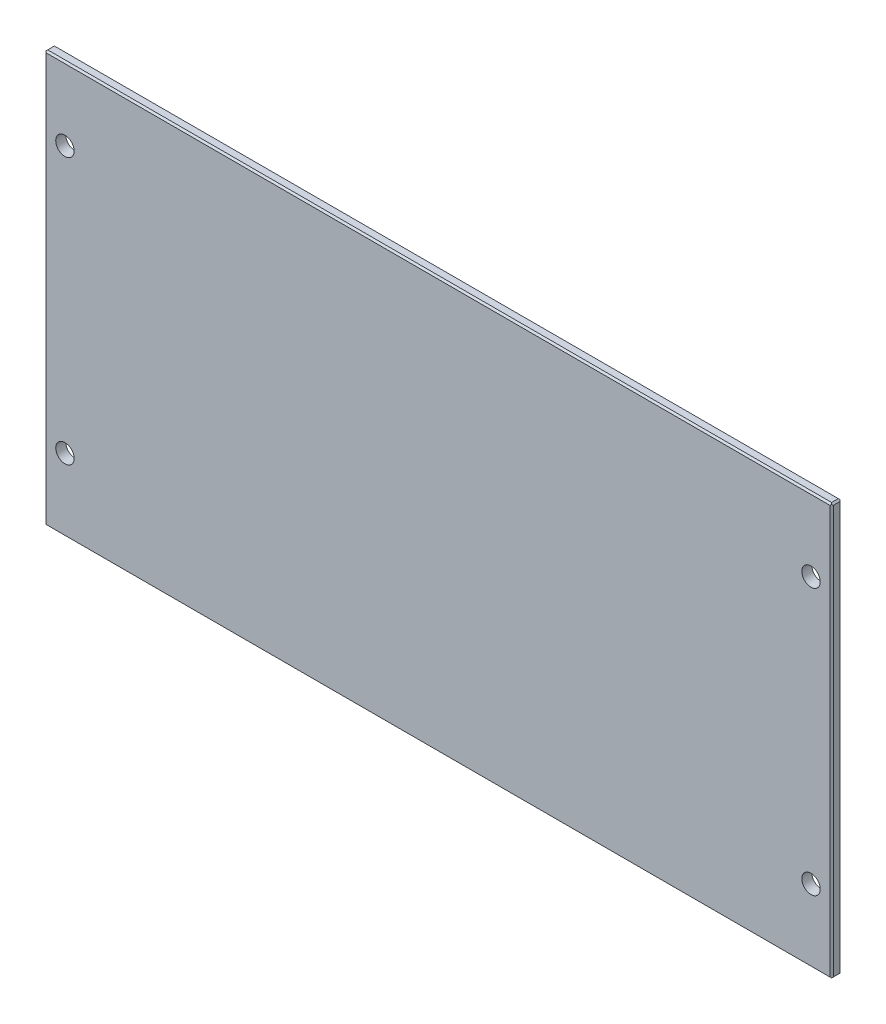
SolidWorks part; units mm, degrees
ref_plane "Front Plane" through (0, 0, 0) normal (0, 0, 1) x (1, 0, 0)
ref_plane "Top Plane" through (0, 0, 0) normal (0, 1, 0) x (1, 0, 0)
ref_plane "Right Plane" through (0, 0, 0) normal (1, 0, 0) x (0, 0, -1)
sketch "Sketch1" plane through (0, 0, 0) normal (0, 0, 1) x (1, 0, 0)
  line L1 (-117.565, 61.5) -> (117.565, 61.5)
  line L2 (-117.565, 61.5) -> (-117.565, -61.5)
  line L3 (-117.565, -61.5) -> (117.565, -61.5)
  line L4 (117.565, 61.5) -> (117.565, -61.5)
  line L5 (-117.565, 61.5) -> (117.565, -61.5) construction
  line L6 (-117.565, -61.5) -> (117.565, 61.5) construction
  point P0 (0, 0)
  dimension "D1" = 235.13
  dimension "D2" = 123
extrude "Boss-Extrude1" add sketch "Sketch1" along normal blind 3
sketch "Sketch2" plane through (0, 0, 3) normal (0, 0, 1) x (1, 0, 0)
  line L0 (-117.565, 61.5) -> (-117.565, -61.5) construction
  line L5 (117.565, 61.5) -> (-117.565, 61.5) construction
  line L6 (55, 0) -> (-55, 0) construction
  line L7 (0, -87.4256) -> (0, 87.4256) construction
  circle A0 centre (-111.415, 39.75) radius 2.75
  circle A1 centre (-111.415, -39.75) radius 2.75
  circle A2 centre (111.415, -39.75) radius 2.75
  circle A3 centre (111.415, 39.75) radius 2.75
  dimension "D2" = 21.75
  dimension "D3" = 5.5
  dimension "D1" = 6.15
extrude "Cut-Extrude1" cut sketch "Sketch2" against normal through all
chamfer "Chamfer1" distance 0.5 angle 45 8 edges at (0, -61.5, 3) (-117.565, 0, 3) (0, 61.5, 3) (117.565, 0, 3) (0, 61.5, 0) (-117.565, 0, 0) (0, -61.5, 0) (117.565, 0, 0)
chamfer "Chamfer2" distance 0.5 angle 45 4 edges at (-117.565, -61.5, 1.5) (117.565, -61.5, 1.5) (117.565, 61.5, 1.5) (-117.565, 61.5, 1.5)
